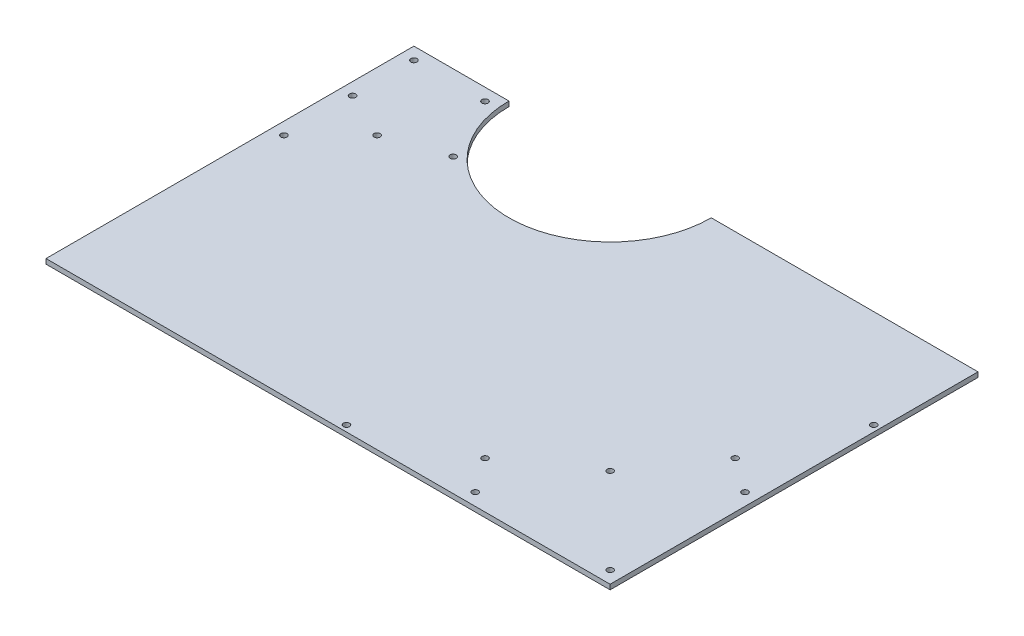
SolidWorks part; units mm, degrees
ref_plane "Front Plane" through (0, 0, 0) normal (0, 0, 1) x (1, 0, 0)
ref_plane "Top Plane" through (0, 0, 0) normal (0, 1, 0) x (1, 0, 0)
ref_plane "Right Plane" through (0, 0, 0) normal (1, 0, 0) x (0, 0, -1)
sketch "Sketch1" plane through (0, 0, 0) normal (0, 1, 0) x (1, 0, 0)
  line L1 (0, 0) -> (381, 0)
  line L2 (0, 0) -> (0, 381)
  line L3 (0, 381) -> (381, 381)
  line L4 (381, 0) -> (381, 381)
  line L5 (0, 381) -> (-203.2, 381)
  line L6 (0, 381) -> (0, 0)
  line L7 (0, 0) -> (-203.2, 0)
  line L8 (-203.2, 381) -> (-203.2, 0)
  arc A0 (381, 381) -> (0, 0) centre (0, 381) cw
  circle A1 centre (39.2386, 142.9117) radius 139.7
  circle A2 centre (0, 381) radius 101.6
  circle A3 centre (196.7476, 241.3) radius 139.7
  circle A4 centre (86.3584, 155.6826) radius 139.7
  circle A5 centre (-59.7956, 143.4044) radius 143.4044
  dimension "D1" = 381
  dimension "D2" = 381
  dimension "D3" = 203.2
sketch "Sketch2" plane through (0, 0, 0) normal (0, 1, 0) x (1, 0, 0)
  line L0 (-203.2, 381) -> (-44.423, 381)
  line L1 (44.0206, 381) -> (381, 381)
  line L2 (-203.2, 381) -> (-203.2, 0)
  line L3 (-203.2, 0) -> (381, 0)
  line L4 (381, 381) -> (381, 0)
  line L6 (-44.423, 381) -> (-44.423, 423.7475)
  line L7 (-44.423, 423.7475) -> (44.0206, 423.7475)
  line L8 (44.0206, 381) -> (44.0206, 423.7475)
extrude "Boss-Extrude1" add sketch "Sketch2" along normal blind 5.08
sketch "Sketch4" plane through (0, 0, 0) normal (0, -1, 0) x (1, 0, 0)
  circle A0 centre (0, -381) radius 104.775
  dimension "D1" = 209.55
extrude "Cut-Extrude1" cut sketch "Sketch4" against normal blind 50.8
sketch "Sketch5" plane through (0, 5.08, 0) normal (0, 1, 0) x (1, 0, 0)
  line L0 (-203.2, 0) -> (381, 0) construction
  line L1 (381, 0) -> (381, 381) construction
  circle A0 centre (332.74, 177.8) radius 3.175
  circle A1 centre (101.6, 6.35) radius 3.175
  circle A2 centre (203.2, 48.26) radius 3.175
  circle A3 centre (279.4, 101.6) radius 3.175
  circle A4 centre (368.3, 152.4) radius 3.175
  circle A5 centre (374.65, 279.4) radius 3.175
  circle A6 centre (368.3, 12.7) radius 3.175
  circle A7 centre (228.6, 12.7) radius 3.175
  dimension "D1" = 6.35
  dimension "D2" = 6.35
  dimension "D3" = 279.4
  dimension "D4" = 12.7
  dimension "D5" = 152.4
  dimension "D6" = 12.7
  dimension "D7" = 12.7
  dimension "D8" = 6.35
  dimension "D9" = 279.4
  dimension "D10" = 12.7
  dimension "D11" = 152.4
  dimension "D12" = 177.8
  dimension "D13" = 48.26
  dimension "D14" = 101.6
  dimension "D15" = 101.6
  dimension "D16" = 48.26
  dimension "D17" = 177.8
extrude "Cut-Extrude2" cut sketch "Sketch5" against normal blind 5.08
sketch "Sketch6" plane through (0, 5.08, 0) normal (0, 1, 0) x (1, 0, 0)
  line L0 (-104.775, 381) -> (-203.2, 381) construction
  line L1 (-203.2, 381) -> (-203.2, 0) construction
  circle A0 centre (-190.5, 368.3) radius 3.175
  circle A1 centre (-116.84, 368.3) radius 3.175
  circle A2 centre (-83.82, 302.26) radius 3.175
  circle A3 centre (-142.24, 281.94) radius 3.175
  circle A4 centre (-190.5, 233.68) radius 3.175
  circle A5 centre (-190.5, 304.8) radius 3.175
  dimension "D1" = 6.35
  dimension "D2" = 12.7
  dimension "D3" = 12.7
  dimension "D4" = 86.36
  dimension "D5" = 12.7
  dimension "D6" = 78.74
  dimension "D7" = 119.38
  dimension "D8" = 60.96
  dimension "D9" = 99.06
  dimension "D10" = 12.7
  dimension "D11" = 147.32
  dimension "D12" = 12.7
  dimension "D13" = 76.2
extrude "Cut-Extrude3" cut sketch "Sketch6" against normal blind 5.08
